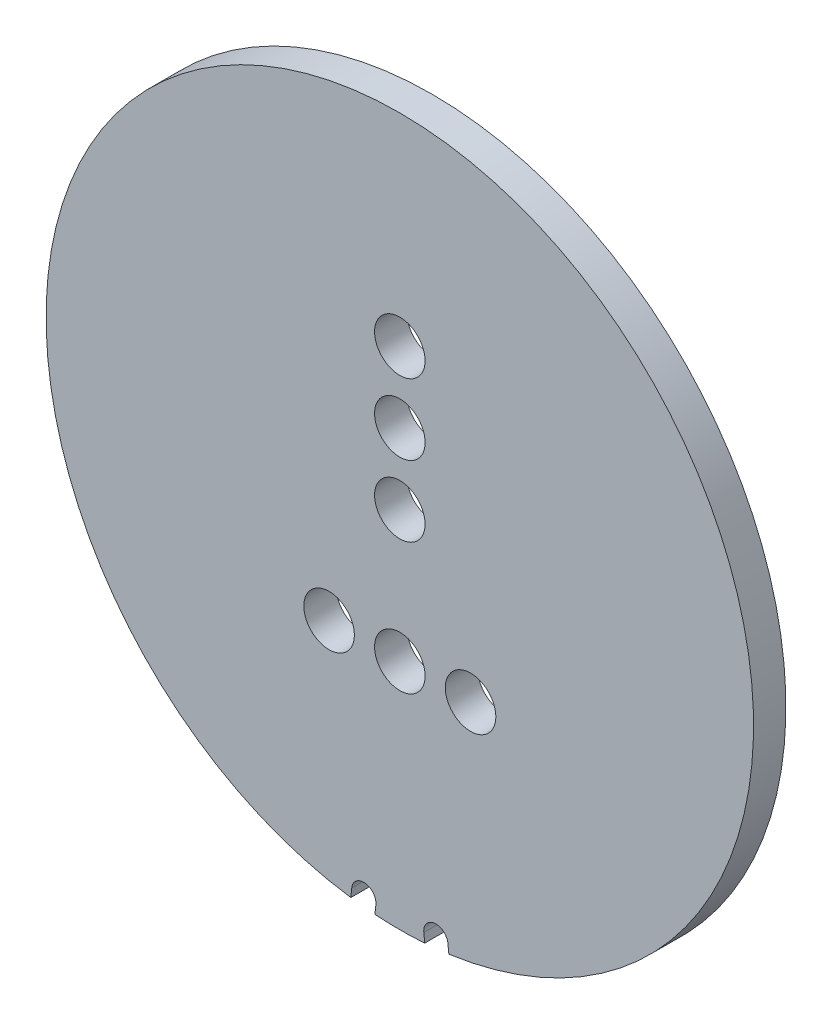
SolidWorks part; units mm, degrees
ref_plane "Front Plane" through (0, 0, 0) normal (0, 0, 1) x (1, 0, 0)
ref_plane "Top Plane" through (0, 0, 0) normal (0, 1, 0) x (1, 0, 0)
ref_plane "Right Plane" through (0, 0, 0) normal (1, 0, 0) x (0, 0, -1)
sketch "Sketch1" plane through (0, 0, -930.4) normal (0, 0, -1) x (-1, 0, 0)
  circle A0 centre (0, 0) radius 17.5
  point P22 (0, 0)
  dimension "D1" = 35
extrude "Boss-Extrude1" add sketch "Sketch1" along normal blind 1.6
sketch "Sketch2" plane through (0, 0, -932) normal (0, 0, -1) x (-1, 0, 0)
  line L0 (0, 17.5) -> (0, 17.05) construction
  line L1 (0.6, 17.5) -> (0.6, 17.05)
  line L2 (-0.6, 17.5) -> (-0.6, 17.05)
  line L3 (-1.2325, -17.4669) -> (0, 0) construction
  line L4 (1.8292, -17.4041) -> (1.7822, -16.9566) construction
  line L5 (1.2325, -17.4669) -> (1.1855, -17.0193)
  line L6 (2.426, -17.3414) -> (2.3789, -16.8939)
  line L7 (0, 0.88) -> (0, -0.88) construction
  line L8 (-1.8292, -17.4041) -> (-1.7822, -16.9566) construction
  line L9 (-1.2325, -17.4669) -> (-1.1855, -17.0193)
  line L10 (-2.426, -17.3414) -> (-2.3789, -16.8939)
  line L11 (0, 0) -> (1.2325, -17.4669) construction
  arc A1 (0.6, 17.5) -> (-0.6, 17.5) centre (0, 17.5) ccw
  arc A2 (-0.6, 17.05) -> (0.6, 17.05) centre (0, 17.05) ccw
  circle A3 centre (0, 0) radius 17.5 construction
  arc A4 (1.2325, -17.4669) -> (2.426, -17.3414) centre (1.8292, -17.4041) ccw
  arc A5 (2.3789, -16.8939) -> (1.1855, -17.0193) centre (1.7822, -16.9566) ccw
  arc A6 (-1.2325, -17.4669) -> (-2.426, -17.3414) centre (-1.8292, -17.4041) cw
  arc A7 (-2.3789, -16.8939) -> (-1.1855, -17.0193) centre (-1.7822, -16.9566) cw
  point P5 (0, 17.275)
  point P13 (1.8057, -17.1804)
  point P20 (0, 0)
  point P23 (-1.8057, -17.1804)
  point P28 (0, 0)
  circle M5 centre (0, 0) radius 17.5
  dimension "D1" = 0.6
  dimension "D2" = 0.45
  dimension "D4" = 12
  dimension "D5" = 8.073
  dimension "D3" = 2
extrude "Cut-Extrude1" cut sketch "Sketch2" against normal through all contours A7 L10 L9 M5 | L6 A5 L5 M5
sketch "Sketch3" plane through (0, 0, -930.4) normal (0, 0, 1) x (1, 0, 0)
  line L0 (2.4249, -17.3312) -> (0, 0) construction
  line L1 (0, 0) -> (0.6, 17.4897) construction
  line L2 (-1.2315, -17.4566) -> (0, 0) construction
  line L3 (0, 0) -> (1.2315, -17.4566) construction
  line L7 (-2.4249, -17.3312) -> (-2.3789, -16.8939)
  line L8 (-1.1855, -17.0193) -> (-1.2315, -17.4566)
  line L9 (1.2315, -17.4566) -> (1.1855, -17.0193)
  line L10 (2.3789, -16.8939) -> (2.4249, -17.3312)
  line L14 (-2.4249, -17.3312) -> (-2.3789, -16.8939)
  line L15 (-1.1855, -17.0193) -> (-1.2315, -17.4566)
  line L16 (1.2315, -17.4566) -> (1.1855, -17.0193)
  line L17 (2.3789, -16.8939) -> (2.4249, -17.3312)
  arc A8 (2.4249, -17.3312) -> (-2.4249, -17.3312) centre (0, 0) ccw
  arc A9 (-1.1855, -17.0193) -> (-2.3789, -16.8939) centre (-1.7822, -16.9566) ccw
  arc A10 (-1.2315, -17.4566) -> (1.2315, -17.4566) centre (0, 0) ccw
  arc A11 (2.3789, -16.8939) -> (1.1855, -17.0193) centre (1.7822, -16.9566) ccw
  arc A38 (2.4249, -17.3312) -> (-2.4249, -17.3312) centre (0, 0) ccw
  arc A39 (-1.1855, -17.0193) -> (-2.3789, -16.8939) centre (-1.7822, -16.9566) ccw
  arc A40 (-1.2315, -17.4566) -> (1.2315, -17.4566) centre (0, 0) ccw
  arc A41 (2.3789, -16.8939) -> (1.1855, -17.0193) centre (1.7822, -16.9566) ccw
  dimension "D2" = 170.07
  dimension "D3" = 8.07
  dimension "D1" = 0
sketch "Sketch4" plane through (0, 0, -930.4) normal (0, 0, 1) x (1, 0, 0)
  circle A0 centre (0, 7.5) radius 1.25
  circle A1 centre (0, 4) radius 1.25
  circle A2 centre (0, 0.5) radius 1.25
  circle A3 centre (-3.5, -6) radius 1.25
  circle A4 centre (0, -6) radius 1.25
  circle A5 centre (3.5, -6) radius 1.25
  dimension "D1" = 2.5
extrude "Cut-Extrude2" cut sketch "Sketch4" against normal through all
sketch "Sketch5" plane through (0, 0, -930.4) normal (0, 0, 1) x (1, 0, 0)
  point P0 (-3.5, -6)
  point P1 (0, 0.5)
  point P3 (0, 0)
  point P6 (0, 4)
